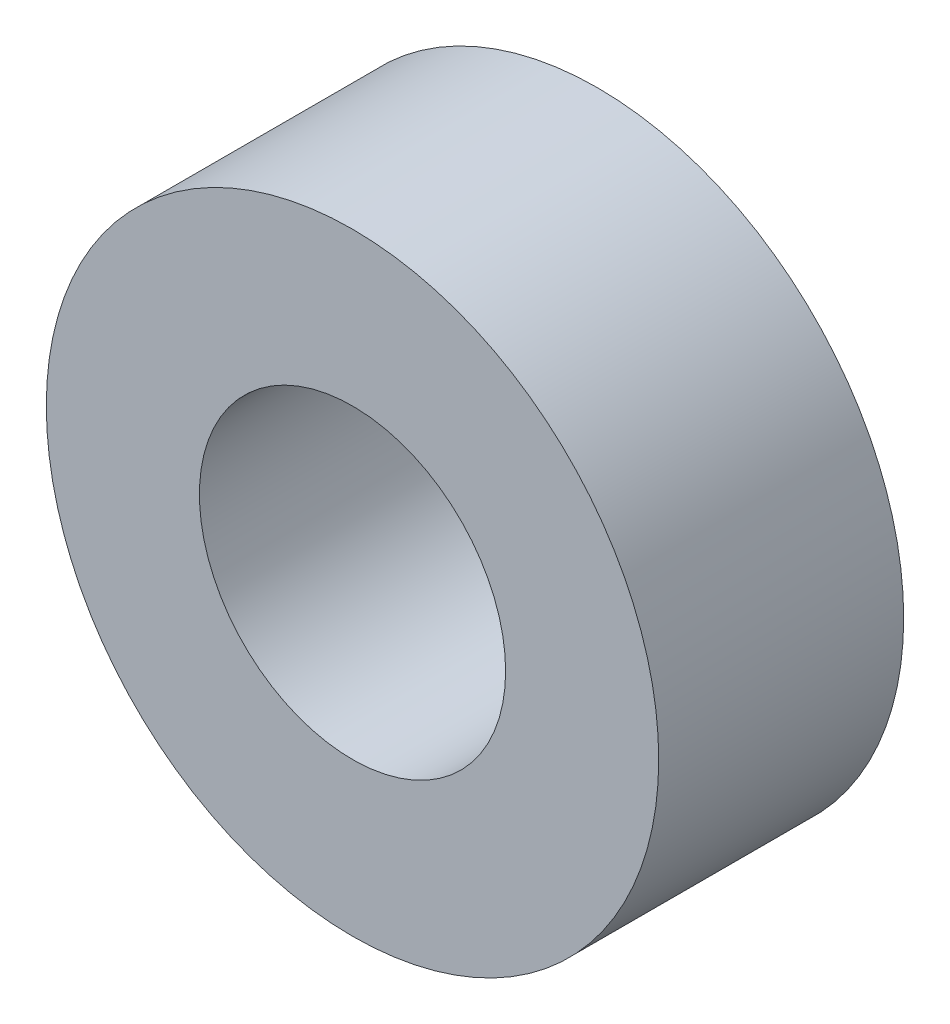
SolidWorks part; units mm, degrees
ref_plane "Front Plane" through (0, 0, 0) normal (0, 0, 1) x (1, 0, 0)
ref_plane "Top Plane" through (0, 0, 0) normal (0, 1, 0) x (1, 0, 0)
ref_plane "Right Plane" through (0, 0, 0) normal (1, 0, 0) x (0, 0, -1)
sketch "Sketch1" plane through (0, 0, 0) normal (0, 0, 1) x (1, 0, 0)
  circle A0 centre (0, 0) radius 5
  circle A1 centre (0, 0) radius 2.5
  dimension "D1" = 5
  dimension "D2" = 10
extrude "Boss-Extrude1" add sketch "Sketch1" along normal blind 4
